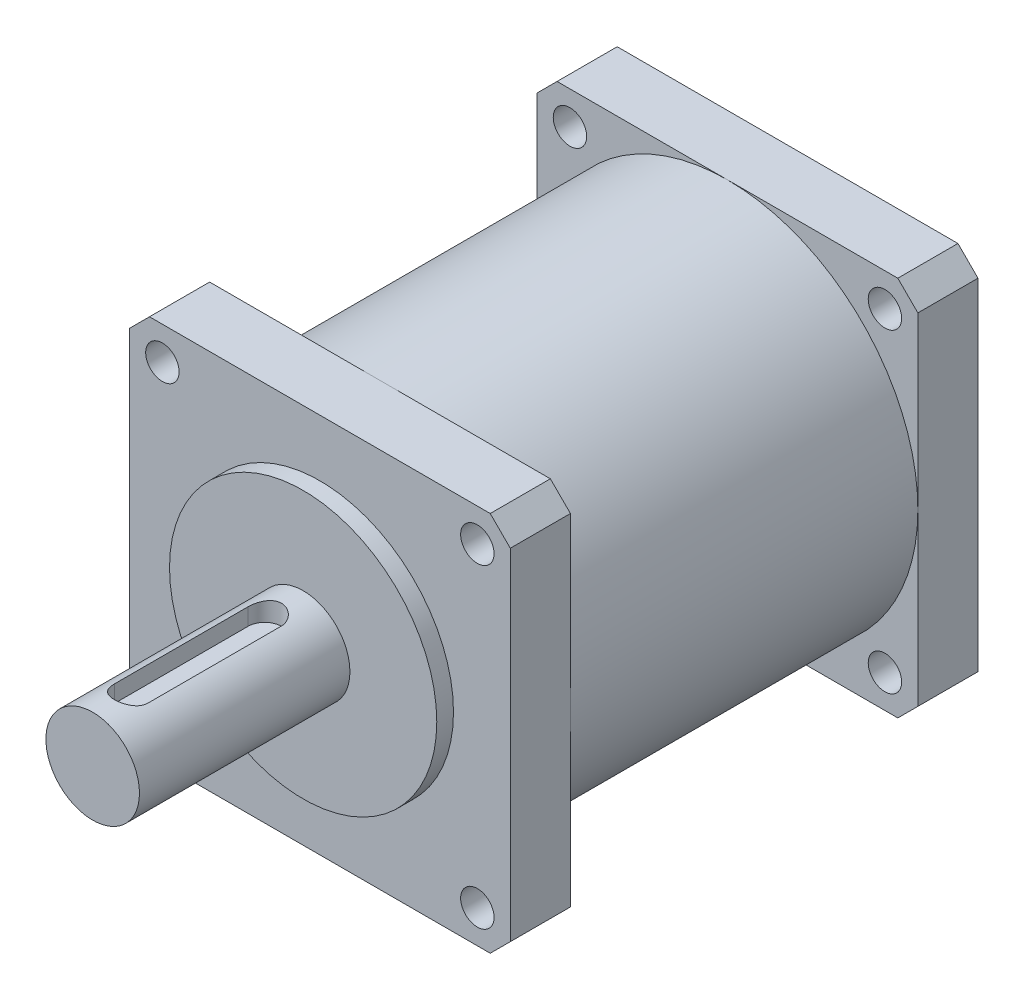
SolidWorks part; units mm, degrees
ref_plane "Front Plane" through (0, 0, 0) normal (0, 0, 1) x (1, 0, 0)
ref_plane "Top Plane" through (0, 0, 0) normal (0, 1, 0) x (1, 0, 0)
ref_plane "Right Plane" through (0, 0, 0) normal (1, 0, 0) x (0, 0, -1)
sketch "Sketch1" plane through (0, 0, 0) normal (0, 0, 1) x (1, 0, 0)
  line L0 (-28.5, -25.5) -> (-25.5, -28.5)
  line L1 (-25.5, 28.5) -> (25.5, 28.5)
  line L2 (-28.5, 25.5) -> (-28.5, -25.5)
  line L3 (-25.5, -28.5) -> (25.5, -28.5)
  line L4 (28.5, 25.5) -> (28.5, -25.5)
  line L5 (-28.5, 28.5) -> (28.5, -28.5) construction
  line L6 (-28.5, -28.5) -> (28.5, 28.5) construction
  line L7 (-28.5, 25.5) -> (-25.5, 28.5)
  line L8 (25.5, 28.5) -> (28.5, 25.5)
  line L9 (25.5, -28.5) -> (28.5, -25.5)
  point P0 (0, 0)
  dimension "D1" = 57
extrude "Boss-Extrude1" add sketch "Sketch1" along normal blind 70
sketch "Sketch2" plane through (0, 0, 0) normal (0, 0, -1) x (-1, 0, 0)
  line L1 (-23.57, 23.57) -> (23.57, 23.57) construction
  line L2 (-23.57, 23.57) -> (-23.57, -23.57) construction
  line L3 (-23.57, -23.57) -> (23.57, -23.57) construction
  line L4 (23.57, 23.57) -> (23.57, -23.57) construction
  line L5 (-23.57, 23.57) -> (23.57, -23.57) construction
  line L6 (-23.57, -23.57) -> (23.57, 23.57) construction
  circle A0 centre (-23.57, 23.57) radius 2.5
  circle A1 centre (-23.57, -23.57) radius 2.5
  circle A2 centre (23.57, -23.57) radius 2.5
  circle A3 centre (23.57, 23.57) radius 2.5
  point P0 (0, 0)
  dimension "D2" = 5
  dimension "D1" = 47.14
extrude "Cut-Extrude1" cut sketch "Sketch2" against normal through all
sketch "Sketch3" plane through (0, 0, 0) normal (1, 0, 0) x (0, 0, -1)
  line L0 (-70, 28.5) -> (0, 28.5) construction
  line L1 (-61, 28.5) -> (-9, 28.5)
  line L2 (-61, 28.5) -> (-61, -28.5)
  line L3 (-61, -28.5) -> (-9, -28.5)
  line L4 (-9, 28.5) -> (-9, -28.5)
  line L5 (-70, -28.5) -> (0, -28.5) construction
  line L6 (0, -25.5) -> (0, 25.5) construction
  line L7 (-70, -25.5) -> (-70, 25.5) construction
  dimension "D1" = 9
  dimension "D2" = 9
extrude "Cut-Extrude2" cut sketch "Sketch3" against normal through all both and the other way through all
sketch "Sketch4" plane through (0, 0, 9) normal (0, 0, 1) x (1, 0, 0)
  circle A0 centre (0, 0) radius 28.5
  dimension "D1" = 57
extrude "Boss-Extrude2" add sketch "Sketch4" along normal up to surface (52 mm away) up to face at (-23.57, 21.07, 61)
sketch "Sketch5" plane through (0, 0, 70) normal (0, 0, 1) x (1, 0, 0)
  circle A0 centre (0, 0) radius 20
  dimension "D1" = 40
extrude "Boss-Extrude3" add sketch "Sketch5" along normal blind 2.5
sketch "Sketch6" plane through (0, 0, 72.5) normal (0, 0, 1) x (1, 0, 0)
  circle A0 centre (0, 0) radius 7
  dimension "D1" = 14
extrude "Boss-Extrude4" add sketch "Sketch6" along normal blind 31.5
ref_plane "Plane1" through (0, 7, 0) normal (0, 1, 0) x (1, 0, 0)
ref_plane "Plane2" through (0, 9, 0) normal (0, 1, 0) x (1, 0, 0)
sketch "Sketch7" plane through (0, 9, 0) normal (0, 1, 0) x (1, 0, 0)
  line L0 (0, -98.25) -> (0, -78.25) construction
  line L1 (-2.5, -98.25) -> (-2.5, -78.25)
  line L2 (2.5, -98.25) -> (2.5, -78.25)
  line L3 (-7, -88.25) -> (0, -88.25) construction
  line L4 (-7, -72.5) -> (-7, -104) construction
  arc A0 (-2.5, -98.25) -> (2.5, -98.25) centre (0, -98.25) ccw
  arc A1 (2.5, -78.25) -> (-2.5, -78.25) centre (0, -78.25) ccw
  point P3 (0, -88.25)
  point P8 (0, -75.75)
  point P9 (0, -100.75)
  dimension "D1" = 5
  dimension "D2" = 25
extrude "Cut-Extrude3" cut sketch "Sketch7" against normal blind 5
